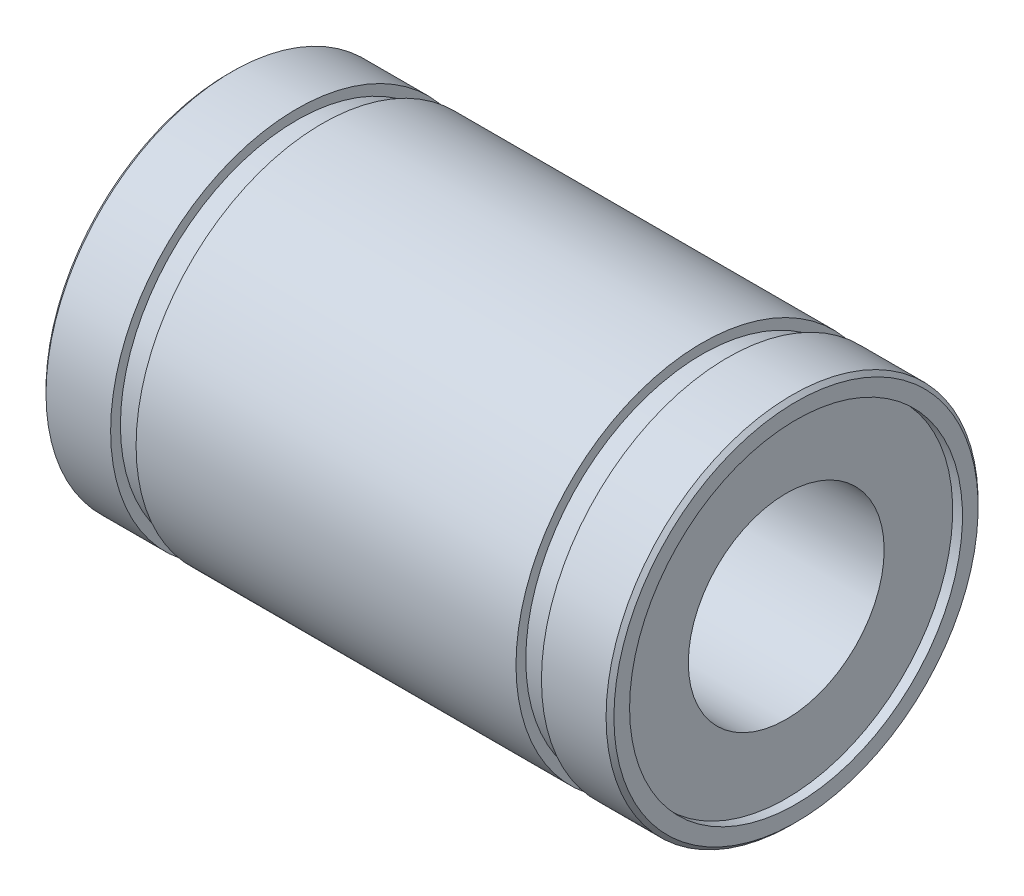
SolidWorks part; units mm, degrees
ref_plane "Front Plane" through (0, 0, 0) normal (0, 0, 1) x (1, 0, 0)
ref_plane "Top Plane" through (0, 0, 0) normal (0, 1, 0) x (1, 0, 0)
ref_plane "Right Plane" through (0, 0, 0) normal (1, 0, 0) x (0, 0, -1)
sketch "Sketch1" plane through (0, 0, 0) normal (0, 0, 1) x (1, 0, 0)
  line L0 (0, 0) -> (112.5581, 0) construction
  line L1 (0.5, 5) -> (0.5, 8.5)
  line L2 (0.5, 8.5) -> (0, 8.5)
  line L3 (0, 8.5) -> (0, 9.5)
  line L4 (0, 9.5) -> (3.5, 9.5)
  line L5 (3.5, 9.5) -> (3.5, 9)
  line L6 (3.5, 9) -> (4.8, 9)
  line L7 (4.8, 9) -> (4.8, 9.5)
  line L8 (4.8, 9.5) -> (24.2, 9.5)
  line L9 (24.2, 9.5) -> (24.2, 9)
  line L10 (24.2, 9) -> (25.5, 9)
  line L11 (25.5, 9) -> (25.5, 9.5)
  line L12 (25.5, 9.5) -> (29, 9.5)
  line L13 (29, 9.5) -> (29, 8.5)
  line L14 (29, 8.5) -> (28.5, 8.5)
  line L15 (28.5, 8.5) -> (28.5, 5)
  line L16 (28.5, 5) -> (0.5, 5)
  dimension "D1" = 10
  dimension "D2" = 19
  dimension "D3" = 1.3
  dimension "D4" = 22
  dimension "D5" = 29
  dimension "D6" = 18
  dimension "D7" = 0.5
revolve "Revolve1" add sketch "Sketch1" angle 360 about L0
chamfer "Chamfer1" distance 0.2 angle 45 2 edges at (29, 0, 9.5) (0, 0, 9.5)
